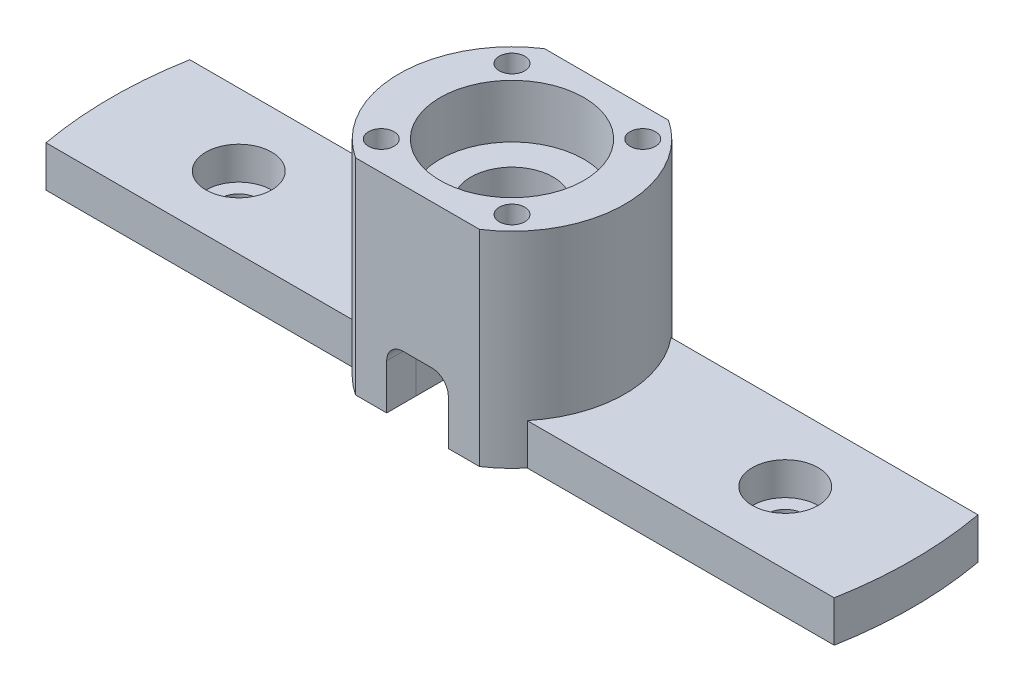
SolidWorks part; units mm, degrees
ref_plane "Front Plane" through (0, 0, 0) normal (0, 0, 1) x (1, 0, 0)
ref_plane "Top Plane" through (0, 0, 0) normal (0, 1, 0) x (1, 0, 0)
ref_plane "Right Plane" through (0, 0, 0) normal (1, 0, 0) x (0, 0, -1)
sketch "Sketch1" plane through (0, 0, 0) normal (1, 0, 0) x (0, 0, -1)
  line L0 (-8.75, 0) -> (-48.75, 0)
  line L1 (-48.75, 0) -> (-48.75, 5)
  line L2 (-48.75, 5) -> (-13.75, 5)
  line L3 (-13.75, 5) -> (-13.75, 25)
  line L4 (-13.75, 25) -> (-8.75, 25)
  line L5 (-8.75, 25) -> (-8.75, 0)
  point P3 (-48.75, 2.5)
  dimension "D1" = 8.75
  dimension "D2" = 35
  dimension "D3" = 5
  dimension "D4" = 25
  dimension "D5" = 5
ref_axis "Axis1" through (0, -1.25, 0) along (0, 1, 0)
revolve "Revolve1" add sketch "Sketch1" angle 360 about axis through (0, -1.25, 0) along (0, 1, 0)
sketch "Sketch2" plane through (0, 0, 0) normal (0, -1, 0) x (1, 0, 0)
  circle A0 centre (0, 0) radius 8.75
  circle A1 centre (0, 0) radius 5
  circle A2 centre (0, 0) radius 8.75 construction
  dimension "D1" = 10
extrude "Boss-Extrude1" add sketch "Sketch2" against normal blind 18.5 separate body
sketch "Sketch3" plane through (0, 5, 0) normal (0, 1, 0) x (1, 0, 0)
  line L0 (-28.9992, 0) -> (32.6868, 0) construction
  line L1 (-50, -8.75) -> (-10.6066, -8.75)
  line L2 (50, 8.75) -> (10.6066, 8.75)
  line L3 (-10.6066, 8.75) -> (-50, 8.75)
  line L4 (10.6066, -8.75) -> (50, -8.75)
  line L5 (50, 8.75) -> (50, 58.75)
  line L6 (50, 58.75) -> (-50, 58.75)
  line L7 (-50, 58.75) -> (-50, 8.75)
  line L8 (-50, -8.75) -> (-50, -58.75)
  line L9 (-50, -58.75) -> (50, -58.75)
  line L10 (50, -58.75) -> (50, -8.75)
  circle A0 centre (0, 0) radius 8.75 construction
  arc A1 (10.6066, 8.75) -> (-10.6066, 8.75) centre (0, 0) ccw
  circle A2 centre (0, 0) radius 13.75 construction
  arc A3 (-10.6066, -8.75) -> (10.6066, -8.75) centre (0, 0) ccw
  point P10 (0, -58.75)
  point P18 (0, 58.75)
  dimension "D1" = 50
  dimension "D2" = 50
  dimension "D3" = 100
  dimension "D4" = 100
extrude "Cut-Extrude1" cut sketch "Sketch3" against normal through all both and the other way through all
sketch "Sketch5" plane through (0, 5, 0) normal (0, 1, 0) x (1, 0, 0)
  line L0 (43.7015, 0) -> (-54.7762, 0) construction
  point P3 (-33.25, 0)
  point P4 (33.25, 0)
  dimension "D1" = 33.25
  dimension "D2" = 33.25
sketch "Sketch8" plane through (0, 5, 0) normal (0, 1, 0) x (1, 0, 0)
  point P0 (-33.25, 0)
  point P3 (33.25, 0)
hole_wizard "CBORE for M4 SHCS1" positions "Sketch8" profile "Sketch9" counterbore size "M4" standard "ANSI Metric" end condition through all
sketch "Sketch9" plane through (-33.25, 5, 0) normal (1, 0, 0) x (0, 0, 1)
  line L0 (0, 0) -> (0, 5)
  line L1 (0, 5) -> (2.25, 5)
  line L3 (2.25, 5) -> (2.25, 4)
  line L4 (2.25, 4) -> (4, 4)
  line L5 (4, 4) -> (4, 0)
  line L7 (4, 0) -> (0, 0)
  line L11 (0, -6.35) -> (0, 107.95) construction
  dimension "Thru Hole Dia." = 4.5
  dimension "Thru Hole Depth" = 5
  dimension "C'Bore Dia." = 8
  dimension "C'Bore Depth" = 4
sketch "Sketch10" plane through (0, 0, -8.75) normal (0, 0, -1) x (-1, 0, 0)
  line L0 (3.75, 7.5) -> (-3.75, 7.5)
  line L1 (-3.75, 7.5) -> (-3.75, 0)
  line L2 (-10.6066, 0) -> (10.6066, 0) construction
  line L3 (-3.75, 0) -> (3.75, 0)
  line L4 (3.75, 0) -> (3.75, 7.5)
  dimension "D1" = 7.5
  dimension "D2" = 7.5
extrude "Cut-Extrude2" cut sketch "Sketch10" against normal through all both and the other way through all
fillet "Fillet2" radius 2 1 edges at (3.75, 7.5, 10.5672)
fillet "Fillet3" radius 2 1 edges at (-3.75, 7.5, 10.5672)
fillet "Fillet4" radius 2 1 edges at (-3.75, 7.5, 5.6064)
fillet "Fillet5" radius 2 1 edges at (3.75, 7.5, 5.6064)
fillet "Fillet6" radius 2 1 edges at (-3.75, 7.5, -5.6064)
fillet "Fillet7" radius 2 1 edges at (-3.75, 7.5, -10.5672)
fillet "Fillet8" radius 2 1 edges at (3.75, 7.5, -10.5672)
fillet "Fillet9" radius 2 1 edges at (3.75, 7.5, -5.6064)
sketch "Sketch11" plane through (0, 25, 0) normal (0, 1, 0) x (1, 0, 0)
  line L4 (0, 0) -> (4.3291, 0) construction
  line L6 (0, 0) -> (7.955, 7.955) construction
  circle A0 centre (0, 0) radius 11.25 construction
  circle A2 centre (0, 0) radius 13.75 construction
  point P0 (0, 0)
  point P7 (7.955, 7.955)
  point P9 (7.955, -7.955)
  point P10 (-7.955, -7.955)
  point P11 (-7.955, 7.955)
  point P12 (0, 0)
  dimension "D1" = 2.5
  dimension "D3" = 45
  dimension "D2" = 4
hole_wizard "Ø1.0mm Dowel Hole1" positions "Sketch11" profile "Sketch12" hole size "Ø1.0" standard "ANSI Metric"
sketch "Sketch12" plane through (-7.955, 25, -7.955) normal (1, 0, 0) x (0, 0, 1)
  line L0 (0, 0) -> (0, 20.9313)
  line L1 (0, 20.9313) -> (1.55, 20)
  line L2 (1.55, 20) -> (1.55, 0)
  line L5 (1.55, 0) -> (0, 0)
  line L10 (0, 20.9313) -> (-1.55, 20) construction
  line L11 (0, -6.35) -> (0, 107.95) construction
  dimension "Hole Dia." = 3.1
  dimension "Hole Depth" = 20
  dimension "Drill Angle" = 118
sketch "Sketch14" plane through (0, 25, 0) normal (0, 1, 0) x (1, 0, 0)
  line L0 (-7.5374, -11.5) -> (7.5374, -11.5)
  line L1 (-7.5374, 11.5) -> (7.5374, 11.5)
  line L2 (-7.5374, -11.5) -> (-7.5374, -15.8288)
  line L3 (-7.5374, -15.8288) -> (7.5374, -15.8288)
  line L4 (7.5374, -15.8288) -> (7.5374, -11.5)
  line L5 (7.5374, 11.5) -> (7.5374, 15.8955)
  line L6 (7.5374, 15.8955) -> (-7.5374, 15.8955)
  line L7 (-7.5374, 15.8955) -> (-7.5374, 11.5)
  line L8 (0, 0) -> (-13.75, 0) construction
  circle A0 centre (0, 0) radius 13.75 construction
  dimension "D1" = 11.5
  dimension "D2" = 4.3288
  dimension "D3" = 4.3955
extrude "Cut-Extrude3" cut sketch "Sketch14" against normal through all both and the other way through all
